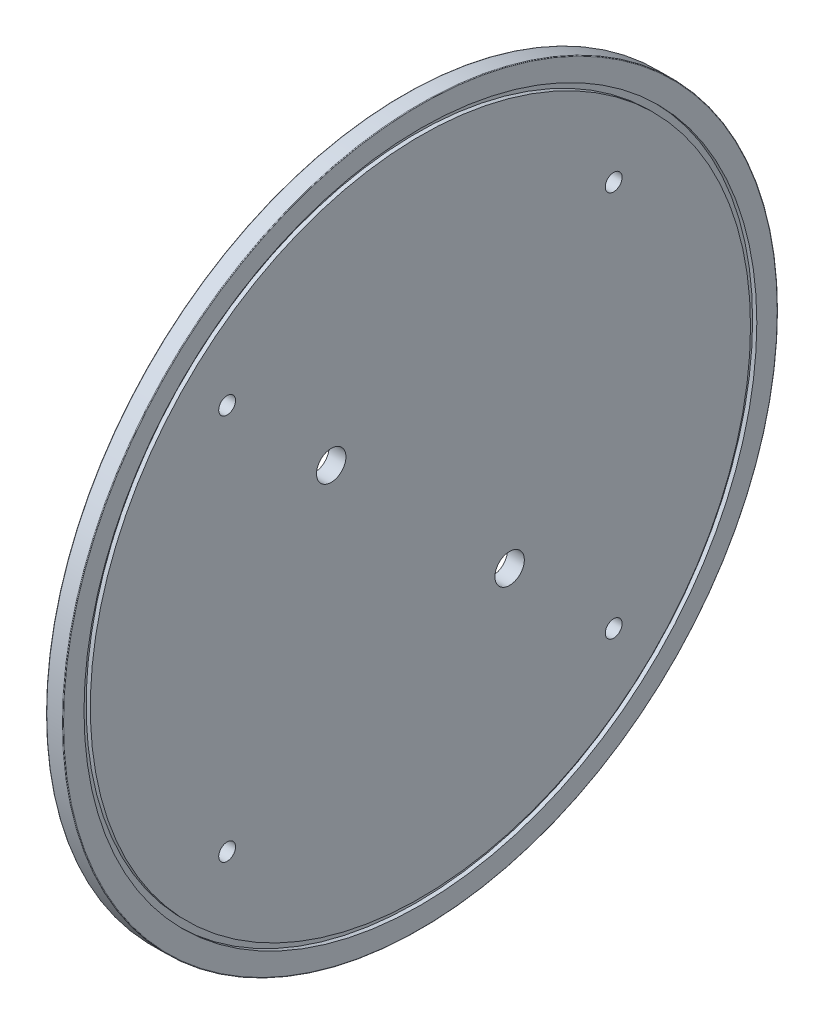
SolidWorks part; units mm, degrees
material "1060 合金"
ref_plane "前视基准面" through (0, 0, 0) normal (0, 0, 1) x (1, 0, 0)
ref_plane "上视基准面" through (0, 0, 0) normal (0, 1, 0) x (1, 0, 0)
ref_plane "右视基准面" through (0, 0, 0) normal (1, 0, 0) x (0, 0, -1)
sketch "草图1" plane through (0, 0, 0) normal (1, 0, 0) x (0, 0, -1)
  circle A0 centre (0, 0) radius 170
extrude "凸台-拉伸1" add sketch "草图1" along normal blind 8
sketch "草图5" plane through (8, 0, 0) normal (1, 0, 0) x (0, 0, -1)
  circle A1 centre (-91.9239, 91.9239) radius 4
extrude "切除-拉伸4" cut sketch "草图5" against normal blind 10
pattern_circular "阵列(圆周)3" count 4 over 360 about axis through (0, 0, 0) along (1, 0, 0) of "切除-拉伸4"
sketch "草图7" plane through (8, 0, 0) normal (1, 0, 0) x (0, 0, -1)
  circle A0 centre (0, 0) radius 157
  circle A1 centre (0, 0) radius 160
extrude "切除-拉伸5" cut sketch "草图7" against normal blind 2
fillet "圆角1" radius 0.3 2 edges at (0, 0, -170) (8, 0, -170)
sketch "草图9" plane through (8, 0, 0) normal (1, 0, 0) x (0, 0, -1)
  circle A3 centre (42.4264, -42.4264) radius 7
extrude "切除-拉伸7" cut sketch "草图9" against normal blind 10
pattern_circular "阵列(圆周)5" count 2 over 360 about axis through (0, 0, 0) along (1, 0, 0) of "切除-拉伸7"
